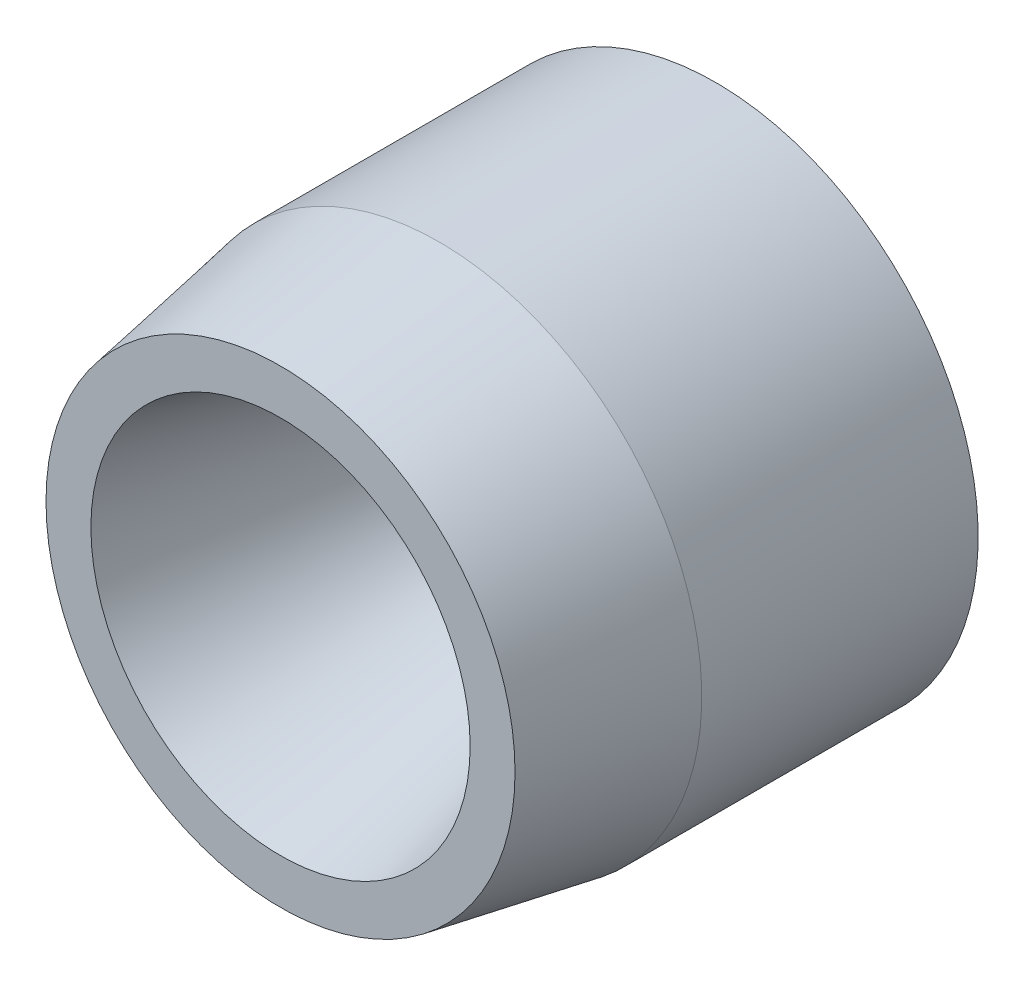
SolidWorks part; units mm, degrees
material "C (Graphite)"
ref_plane "Front Plane" through (0, 0, 0) normal (0, 0, 1) x (1, 0, 0)
ref_plane "Top Plane" through (0, 0, 0) normal (0, 1, 0) x (1, 0, 0)
ref_plane "Right Plane" through (0, 0, 0) normal (1, 0, 0) x (0, 0, -1)
sketch "Sketch1" plane through (0, 0, 0) normal (0, 1, 0) x (1, 0, 0)
  line L0 (44.3992, 143.4985) -> (41.8592, 143.4985)
  line L1 (41.8592, 143.4985) -> (18.415, 129.963)
  line L2 (18.415, 129.963) -> (18.415, 128.4965)
  line L3 (18.415, 128.4965) -> (44.3992, 143.4985)
  line L19 (32.0739, 69.9008) -> (18.415, 120.8765)
  line L20 (40.5949, 38.1) -> (32.0875, 69.85) construction
  line L21 (18.415, 120.8765) -> (18.415, 128.4965)
  line L24 (-39.7075, 69.9008) -> (39.6649, 69.9008)
  line L25 (39.6649, 69.9008) -> (40.7772, 76.2088)
  line L26 (40.7772, 76.2088) -> (44.3992, 96.7504)
  line L27 (44.3992, 96.7504) -> (44.3992, 114.3)
  line L28 (44.3992, 114.3) -> (44.3992, 143.5279)
  line L29 (32.0739, 69.9008) -> (39.6649, 69.9008)
  line L30 (39.6649, 69.9008) -> (40.7772, 76.2088)
  line L31 (40.7772, 76.2088) -> (44.3992, 96.7504)
  line L32 (44.3992, 96.7504) -> (44.3992, 114.3)
  line L33 (44.3992, 114.3) -> (44.3992, 143.4985)
  line L36 (44.3992, 143.4985) -> (18.415, 128.4965)
  line L37 (44.45, 143.5279) -> (59.817, 152.4) construction
  dimension "D2" = 18.415
  dimension "D3" = 1.27
  dimension "D1" = 0.0508
ref_axis "Axis1" through (0, 0, -147.1784) along (0, 0, 1)
revolve "Revolve1" add sketch "Sketch1" angle 360 about axis through (0, 0, -147.1784) along (0, 0, 1)
